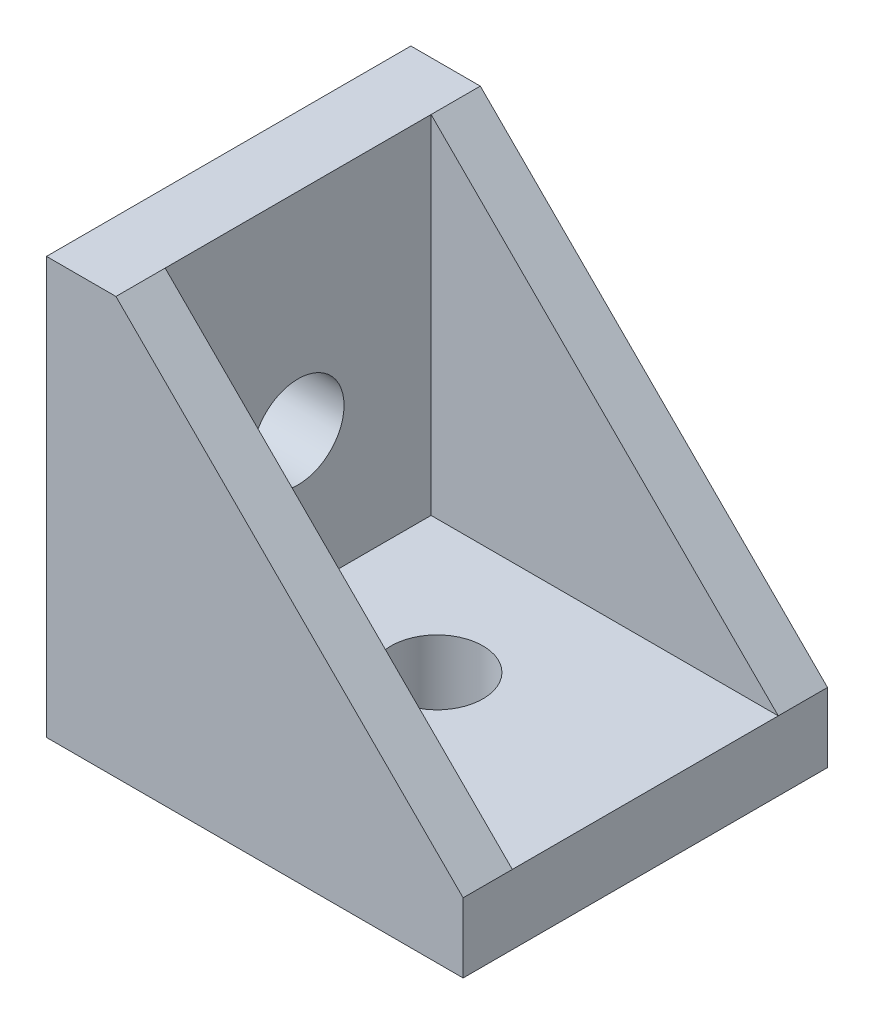
SolidWorks part; units mm, degrees
ref_plane "Front Plane" through (0, 0, 0) normal (0, 0, 1) x (1, 0, 0)
ref_plane "Top Plane" through (0, 0, 0) normal (0, 1, 0) x (1, 0, 0)
ref_plane "Right Plane" through (0, 0, 0) normal (1, 0, 0) x (0, 0, -1)
ref_plane "Plane_zm16_66" through (0, 0, -16.66) normal (0, 0, 1) x (1, 0, 0)
sketch "Sketch1" plane through (0, 0, -16.66) normal (0, 0, 1) x (1, 0, 0)
  line L0 (0, 0) -> (38.1, 0)
  line L1 (38.1, 0) -> (38.1, 6.35)
  line L2 (38.1, 6.35) -> (6.35, 38.1)
  line L3 (6.35, 38.1) -> (0, 38.1)
  line L4 (0, 38.1) -> (0, 0)
extrude "Body" add sketch "Sketch1" along normal blind 33.32
ref_plane "Plane_z12_16" through (0, 0, 12.16) normal (0, 0, 1) x (1, 0, 0)
sketch "Sketch2" plane through (0, 0, 12.16) normal (0, 0, 1) x (1, 0, 0)
  line L0 (6.35, 6.35) -> (48.1, 6.35)
  line L1 (48.1, 6.35) -> (6.35, 48.1)
  line L2 (6.35, 48.1) -> (6.35, 6.35)
extrude "Pocket" cut sketch "Sketch2" against normal blind 24.32
ref_plane "Plane_y6_35" through (0, 6.35, 0) normal (0, 1, 0) x (1, 0, 0)
sketch "Sketch3" plane through (0, 6.35, 0) normal (0, 1, 0) x (1, 0, 0)
  circle A0 centre (19.05, 0) radius 4.2
extrude "HolesX" cut sketch "Sketch3" against normal blind 6.35
ref_plane "Plane_x6_35" through (6.35, 0, 0) normal (1, 0, 0) x (0, 0, -1)
sketch "Sketch4" plane through (6.35, 0, 0) normal (1, 0, 0) x (0, 0, -1)
  circle A0 centre (0, 19.05) radius 4.2
extrude "HolesY" cut sketch "Sketch4" against normal blind 6.35
